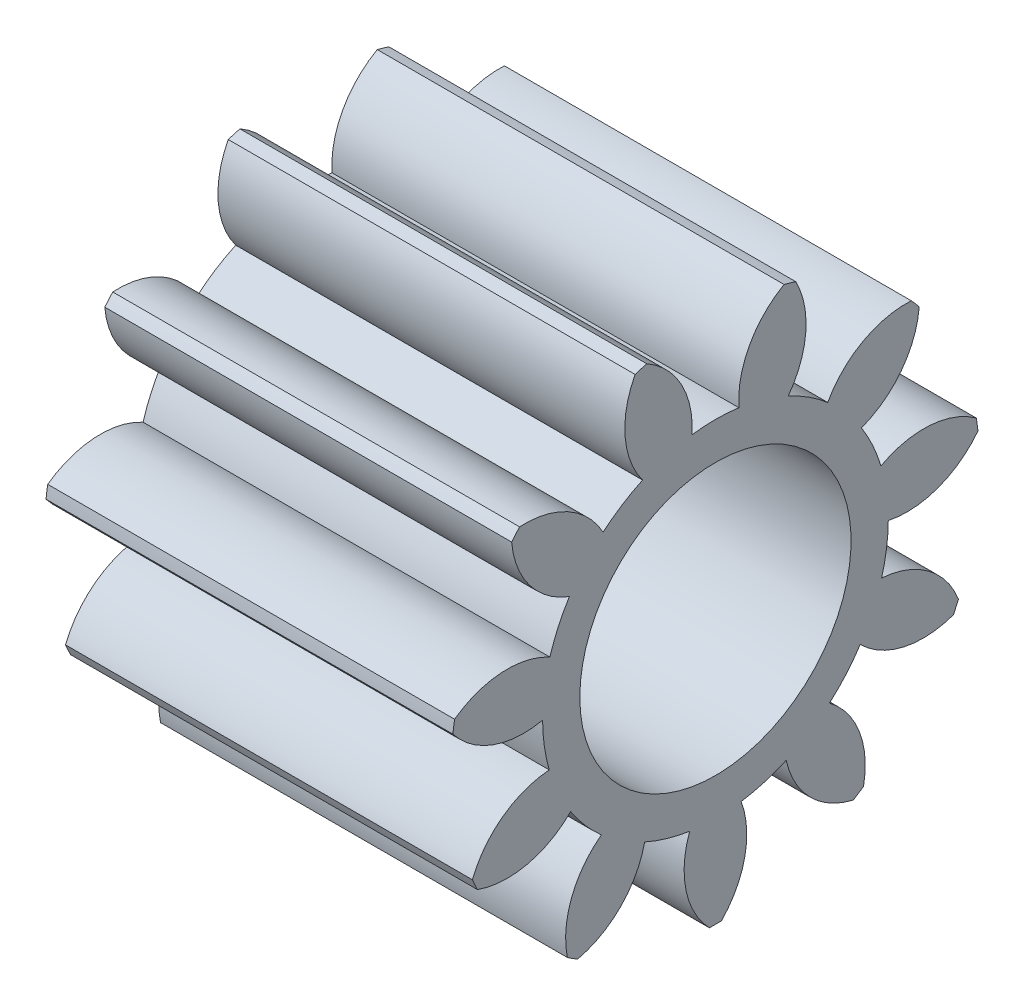
SolidWorks part; units mm, degrees
ref_plane "Plane1" through (0, 0, 0) normal (0, 0, 1) x (1, 0, 0)
ref_plane "Plane2" through (0, 0, 0) normal (0, 1, 0) x (1, 0, 0)
ref_plane "Plane3" through (0, 0, 0) normal (1, 0, 0) x (0, 0, -1)
sketch "HoldingSke" plane through (0, 0, 0) normal (0, 1, 0) x (1, 0, 0)
  line L0 (0, 0) -> (1.636, -0.318)
  line L1 (-15, 0) -> (100, 0) construction
  line L2 (0, 0) -> (-2.1039, 2.3779)
  line L3 (0, 0) -> (-11.863, 4.5341)
  line L4 (0, 0) -> (8.4773, 1.6478)
  line L5 (0, 0) -> (-46.8476, -17.4728)
  line L6 (0, 0) -> (-4.9738, -3.3558)
  line L7 (-2.1039, 2.3779) -> (8.6586, 51.2059)
  line L8 (-76.2, 54.61) -> (-75.5, 54.61)
  line L9 (-71.009, 38.7566) -> (-53.1078, 45.2721)
  line L10 (-76.2, 71.12) -> (104.1128, 71.12)
  line L11 (0, 0) -> (-6, 0)
  line L12 (-76.2, 101.6) -> (-76.177, 101.6)
  line L13 (24.9733, 27.94) -> (52.9518, 28.4284)
  line L14 (24.9733, 27.94) -> (24.9743, 27.94)
  line L15 (24.9733, 27.94) -> (100.4006, 29.5858)
  line L16 (-63.627, -0.6) -> (-12.827, -0.6)
  circle A0 centre (0, 0) radius 2
  circle A1 centre (0, 0) radius 2.549
  circle A2 centre (0, 0) radius 37.5
  circle A3 centre (0, 0) radius 2
  dimension "MHD" = 5.098
  dimension "Hub_dia" = 75
  dimension "Bore" = 4
  dimension "MBD" = 4
  dimension "Num_teeth" = 11
  dimension "Pitch" = 1.6667
  dimension "Overall_len" = 50
  dimension "Show_teeth" = 11
  dimension "Thickness" = 6
  dimension "OAL" = 50.0001
  dimension "T_dim" = 0.7
  dimension "Ap" = 20
  dimension "H" = 19.05
  dimension "Pitch_radius" = 180.3128
  dimension "Width" = 6
  dimension "Backlash" = 0.023
  dimension "Addendum_fac" = 1
  dimension "Dedendum_fac" = 1.25
  dimension "Clearance_fac" = 0.25
  dimension "Dedendum_add" = 0.001
  dimension "Module" = 0.6
sketch "BasProSke" plane through (0, 0, 0) normal (0, 1, 0) x (1, 0, 0)
  line L0 (-10, 0) -> (60, 0) construction
  line L1 (0, 0) -> (0, 3.9)
  line L2 (0, 0) -> (6, 0)
  line L3 (6, 0) -> (6, 3.9)
  line L4 (6, 3.9) -> (0, 3.9)
  dimension "Thickness" = 6
  dimension "Diameter" = 7.8
revolve "Base-Revolve" add sketch "BasProSke" angle 360 about L0
sketch "TooCutSke" plane through (0, 0, 0) normal (1, 0, 0) x (0, 0, -1)
  line L1 (0, 0) -> (0, 107) construction
  line L2 (0, 0) -> (-0.5098, 3.2604) construction
  line L3 (0, 0) -> (-1.8436, 6.2788) construction
  line L4 (-0.5098, 3.2604) -> (-0.9218, 3.1394) construction
  arc A0 (0.3459, 2.5254) -> (-0.3459, 2.5254) centre (0, 0) ccw
  arc A1 (1.0446, 3.7839) -> (-1.0446, 3.7839) centre (0, 0) ccw
  circle A2 centre (0, 0) radius 3.3 construction
  circle A3 centre (0, 0) radius 3.101 construction
  arc A4 (-0.3459, 2.5254) -> (-1.0446, 3.7839) centre (-1.6627, 2.6175) ccw
  arc A5 (1.0446, 3.7839) -> (0.3459, 2.5254) centre (1.6627, 2.6175) ccw
  dimension "Root_dia" = 5.098
  dimension "Overcut_dia" = 7.8508
  dimension "Pitch_dia" = 6.6
  dimension "Base_dia" = 6.202
  dimension "Flank_rad" = 1.32
  dimension "Half_ang" = 16.364
  dimension "Half_CT" = 0.4294
extrude "ToothCut" cut sketch "TooCutSke" along normal through all
fillet "Breaks" [suppressed] radius 0.012
fillet "RootFillets" [suppressed] radius 0.151
pattern_circular "TeethCuts" count 11 every 32.727 about axis through (-10, 0, 0) along (1, 0, 0) of "ToothCut", "RootFillets", "Breaks"
sketch "HubNeaOneSke" plane through (0, 0, 0) normal (-1, 0, 0) x (0, 0, 1)
  circle A0 centre (0, 0) radius 2.549
  dimension "Diameter" = 5.098
extrude "HubNearOne" [suppressed] add sketch "HubNeaOneSke" along normal blind 44.0001
sketch "HubNeaBotSke" plane through (0, 0, 0) normal (-1, 0, 0) x (0, 0, 1)
  circle A0 centre (0, 0) radius 2.549
  dimension "Diameter" = 5.098
extrude "HubNearBoth" [suppressed] add sketch "HubNeaBotSke" along normal blind 22
ref_plane "FarPln" through (6, 0, 0) normal (1, 0, 0) x (0, 0, -1)
sketch "HubFarSke" plane through (6, 0, 0) normal (1, 0, 0) x (0, 0, -1)
  circle A0 centre (0, 0) radius 2.549
  dimension "Diameter" = 5.098
extrude "HubFar" [suppressed] add sketch "HubFarSke" along normal blind 22
sketch "BorSke" plane through (0, 0, 0) normal (1, 0, 0) x (0, 0, -1)
  circle A0 centre (0, 0) radius 2
  dimension "Diameter" = 4
extrude "Bore" cut sketch "BorSke" along normal mid plane 100.0001
sketch "KeySke" plane through (0, 0, 0) normal (1, 0, 0) x (0, 0, -1)
  line L0 (-0.8, 0) -> (-0.8, 2.7)
  line L1 (-0.8, 2.7) -> (0.8, 2.7)
  line L2 (0.8, 2.7) -> (0.8, 0)
  line L3 (0, 0) -> (0, 34) construction
  line L4 (-0.8, 0) -> (0.8, 0)
  dimension "Offset" = 2.7
  dimension "Width" = 1.6
extrude "Keyway" [suppressed] cut sketch "KeySke" along normal mid plane 100.0001
pattern_circular "Keyway2" [suppressed] count 2 every 90 about axis through (-10, 0, 0) along (1, 0, 0)
equation "' \"Module@HoldingSke\" = 6.35"
equation "' \"Num_teeth@HoldingSke\" = 12"
equation "' \"Ap@HoldingSke\" =  20"
equation "' \"Ap@HoldingSke\" = 20"
equation "' \"Width@HoldingSke\" = 0.5 * 25.4"
equation "' \"Hub_dia@HoldingSke\"= 1 * 25.4"
equation "' \"Hub_dia@HoldingSke\" = 1 * 25.4"
equation "' \"Overall_len@HoldingSke\" = 1.0 * 25.4"
equation "' \"Bore@HoldingSke\" = 0.75 * 25.4"
equation "' \"T_dim@HoldingSke\" = 0.1 * 25.4"
equation "' \"Width@KeySke\" = 0.25 * 25.4"
equation "' \"Show_teeth@HoldingSke\" = 13"
equation "' \"Backlash@HoldingSke\" = 0.009 * 25.4"
equation "' \"Addendum_fac@HoldingSke\" = 1.0"
equation "' \"Dedendum_fac@HoldingSke\" = 1.25"
equation "' \"Dedendum_add@HoldingSke\" = 0.00005 * 25.4"
equation "' \"Clearance_fac@HoldingSke\" = 0.25"
equation "\"Pitch@HoldingSke\" = 1 / \"Module@HoldingSke\""
equation "\"Overcut_dia@TooCutSke\" = (\"Num_teeth@HoldingSke\" + 2 * \"Addendum_fac@HoldingSke\") / \"Pitch@HoldingSke\" + 0.002 * 25.4"
equation "\"Pitch_dia@TooCutSke\" = \"Num_teeth@HoldingSke\" / \"Pitch@HoldingSke\""
equation "\"Base_dia@TooCutSke\" = \"Num_teeth@HoldingSke\" / \"Pitch@HoldingSke\" * cos((\"Ap@HoldingSke\"  * 3.14159265 / 180))"
equation "\"Root_dia@TooCutSke\" = (\"Num_teeth@HoldingSke\" + 2) / \"Pitch@HoldingSke\" - 2 * (\"Addendum_fac@HoldingSke\" + \"Dedendum_fac@HoldingSke\") / \"Pitch@HoldingSke\" - \"Dedendum_add@HoldingSke\" * 2"
equation "\"Half_ang@TooCutSke\" = 180 / \"Num_teeth@HoldingSke\""
equation "\"Half_CT@TooCutSke\" = \"Num_teeth@HoldingSke\" / \"Pitch@HoldingSke\" * sin((3.14159265 / 2 / \"Num_teeth@HoldingSke\")) / 2 - 7 * \"Backlash@HoldingSke\" / 4"
equation "\"Flank_rad@TooCutSke\" = \"Num_teeth@HoldingSke\" / \"Pitch@HoldingSke\" / 5"
equation "\"Radius@RootFillets\" = \"Clearance_fac@HoldingSke\" / \"Pitch@HoldingSke\" + \"Dedendum_add@HoldingSke\""
equation "\"Break_rad@Breaks\" = 0.02 / \"Pitch@HoldingSke\""
equation "\"Thickness@HoldingSke\" = \"Width@HoldingSke\""
equation "\"OAL@HoldingSke\" = \"Thickness@HoldingSke\""
equation "\"MHD@HoldingSke\" = (\"Num_teeth@HoldingSke\" + 2) / \"Pitch@HoldingSke\" - 2 * (\"Addendum_fac@HoldingSke\" + \"Dedendum_fac@HoldingSke\")  / \"Pitch@HoldingSke\" - \"Dedendum_add@HoldingSke\" * 2"
equation "\"MBD@HoldingSke\" = (\"Num_teeth@HoldingSke\" + 2) / \"Pitch@HoldingSke\" - 2 * (\"Addendum_fac@HoldingSke\" + \"Dedendum_fac@HoldingSke\")  / \"Pitch@HoldingSke\" - \"Dedendum_add@HoldingSke\" * 2 - 0.002 * 25.4"
equation "\"MHD@HoldingSke\" = ((sgn( \"MHD@HoldingSke\" - \"Hub_dia@HoldingSke\" )-1)*( \"MHD@HoldingSke\" - \"Hub_dia@HoldingSke\" ))/-2+ \"Hub_dia@HoldingSke\""
equation "\"MBD@HoldingSke\" = ((sgn( \"MBD@HoldingSke\" - \"Bore@HoldingSke\" )-1)*( \"MBD@HoldingSke\" - \"Bore@HoldingSke\" ))/-2+ \"Bore@HoldingSke\""
equation "\"OAL@HoldingSke\" = ((sgn( \"OAL@HoldingSke\" - \"Overall_len@HoldingSke\" )+1)*( \"OAL@HoldingSke\" - \"Overall_len@HoldingSke\" ))/2 + \"Overall_len@HoldingSke\" + 0.000002 * 25.4"
equation "\"Num_teeth@TeethCuts\" = int( \"Show_teeth@HoldingSke\" ) + 1"
equation "\"Num_teeth@TeethCuts\" = ((sgn( \"Num_teeth@TeethCuts\" - \"Num_teeth@HoldingSke\" )-1)*( \"Num_teeth@TeethCuts\" - \"Num_teeth@HoldingSke\" ))/-2+ \"Num_teeth@HoldingSke\""
equation "\"Num_teeth@TeethCuts\" = ((sgn( \"Num_teeth@TeethCuts\" - 2.0)+1)*( \"Num_teeth@TeethCuts\" - 2.0))/2 +2.0"
equation "\"Angle@TeethCuts\" = 360.0 / \"Num_teeth@HoldingSke\""
equation "\"Diameter@BasProSke\" = (\"Num_teeth@HoldingSke\" + 2 * \"Addendum_fac@HoldingSke\") / \"Pitch@HoldingSke\""
equation "\"Thickness@BasProSke\"  = \"Thickness@HoldingSke\""
equation "' \"Fillet_rad@BasProSke\" =  \"Thickness@HoldingSke\" * 0.05"
equation "' \"Fillet_rad@BasProSke\" = \"Thickness@HoldingSke\" * 0.05"
equation "\"MHD@HoldingSke\" = ((sgn( \"MHD@HoldingSke\" - \"Root_dia@TooCutSke\" )-1)*( \"MHD@HoldingSke\" - \"Root_dia@TooCutSke\" ))/-2+ \"Root_dia@TooCutSke\""
equation "\"Diameter@HubNeaOneSke\" = \"MHD@HoldingSke\""
equation "\"Length@HubNearOne\" = \"OAL@HoldingSke\" - \"Thickness@BasProSke\""
equation "\"Diameter@HubNeaBotSke\" = \"MHD@HoldingSke\""
equation "\"Length@HubNearBoth\" = ( \"OAL@HoldingSke\" - \"Thickness@BasProSke\" ) / 2.0"
equation "\"Thickness@FarPln\" = \"Thickness@BasProSke\""
equation "\"Diameter@HubFarSke\" = \"MHD@HoldingSke\""
equation "\"Length@HubFar\" = ( \"OAL@HoldingSke\" - \"Thickness@BasProSke\" ) / 2.0"
equation "\"Diameter@BorSke\" = \"MBD@HoldingSke\""
equation "\"D1@Bore\" = \"OAL@HoldingSke\" * 2.0"
equation "\"D1@Keyway\" = \"OAL@HoldingSke\" * 2.0"
equation "\"Offset@KeySke\" = \"T_dim@HoldingSke\" + \"MBD@HoldingSke\" / 2.0"
